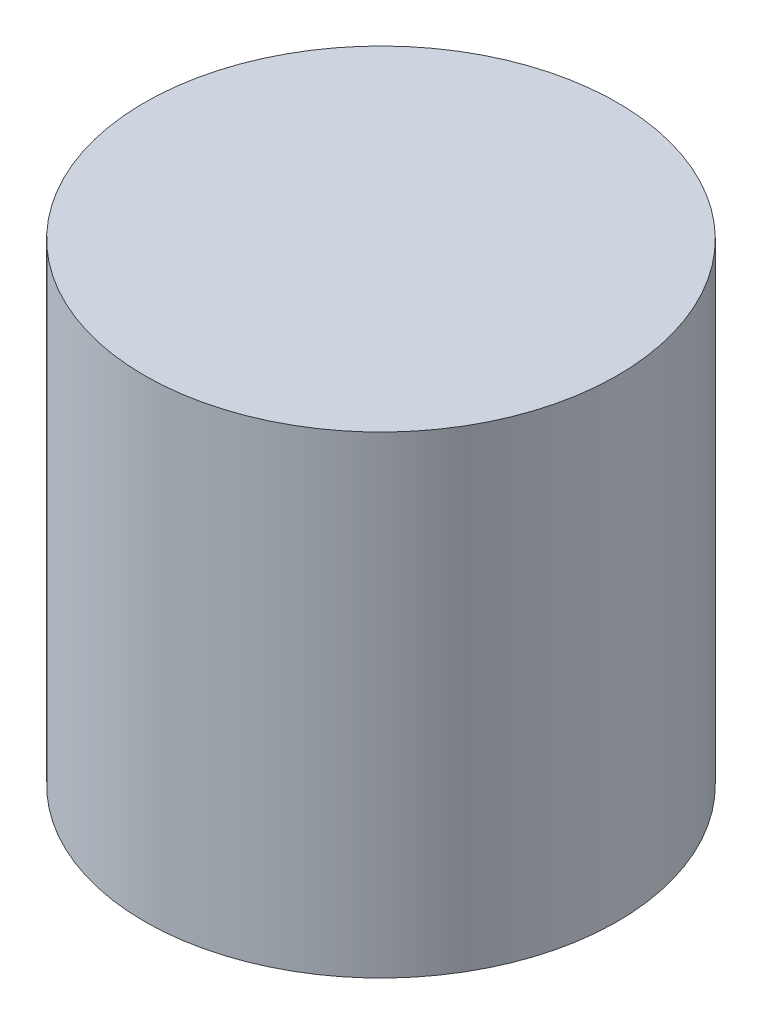
SolidWorks part; units mm, degrees
ref_plane "Front Plane" through (0, 0, 0) normal (0, 0, 1) x (1, 0, 0)
ref_plane "Top Plane" through (0, 0, 0) normal (0, 1, 0) x (1, 0, 0)
ref_plane "Right Plane" through (0, 0, 0) normal (1, 0, 0) x (0, 0, -1)
sketch "Sketch1" plane through (0, 0, 0) normal (0, 1, 0) x (1, 0, 0)
  circle A0 centre (0, 0) radius 3.1242
  dimension "D1" = 6.2484
extrude "Boss-Extrude1" add sketch "Sketch1" along normal blind 6.2484
